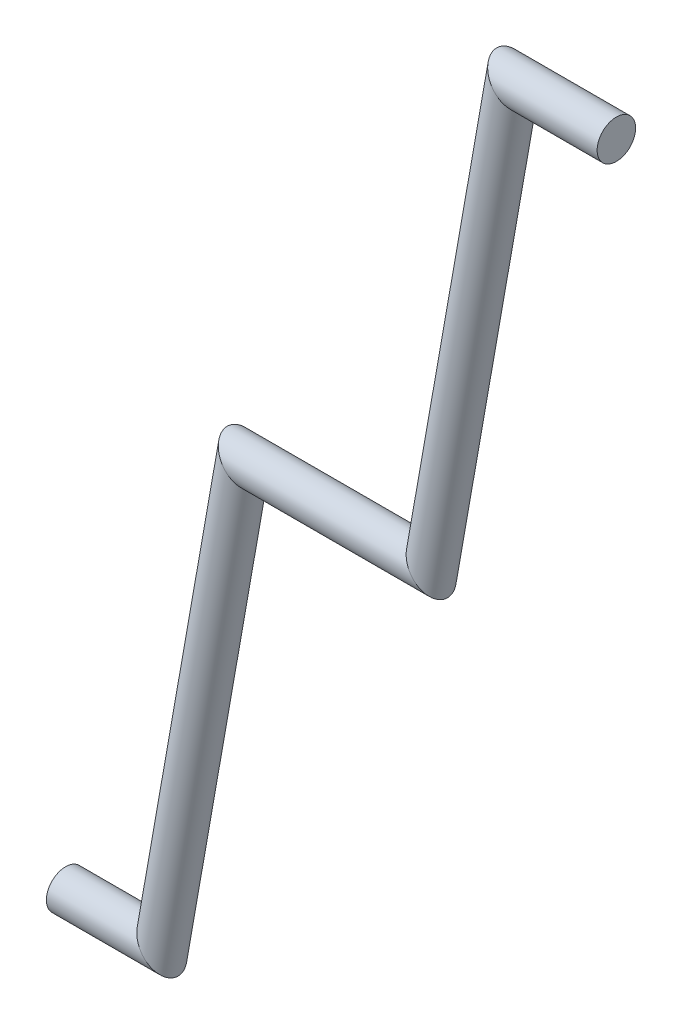
SolidWorks part; units mm, degrees
ref_plane "Front" through (0, 0, 0) normal (0, 0, 1) x (1, 0, 0)
ref_plane "Top" through (0, 0, 0) normal (0, 1, 0) x (1, 0, 0)
ref_plane "Right" through (0, 0, 0) normal (1, 0, 0) x (0, 0, -1)
sketch "Sketch4" plane through (0, 0, 0) normal (1, 0, 0) x (0, 0, -1)
  circle A0 centre (0, 0) radius 6.35
  dimension "D1" = 12.7
sketch "Sketch5" plane through (0, 0, 0) normal (0, 0, 1) x (1, 0, 0)
  line L0 (0, 0) -> (31.75, 0)
  line L1 (31.75, 0) -> (58.6222, 152.4)
  line L2 (58.6222, 152.4) -> (90.3722, 152.4)
  line L3 (90.3722, 152.4) -> (90.3722, 211.8411) construction
  line L4 (90.3722, 152.4) -> (120.549, 152.4)
  line L5 (120.549, 152.4) -> (147.4212, 304.8)
  line L6 (147.4212, 304.8) -> (181.5513, 304.8)
  dimension "D1" = 31.75
  dimension "D2" = 152.4
  dimension "D3" = 31.75
  dimension "D4" = 100
sweep "Sweep3" add profiles "Sketch4" path "Sketch5"
